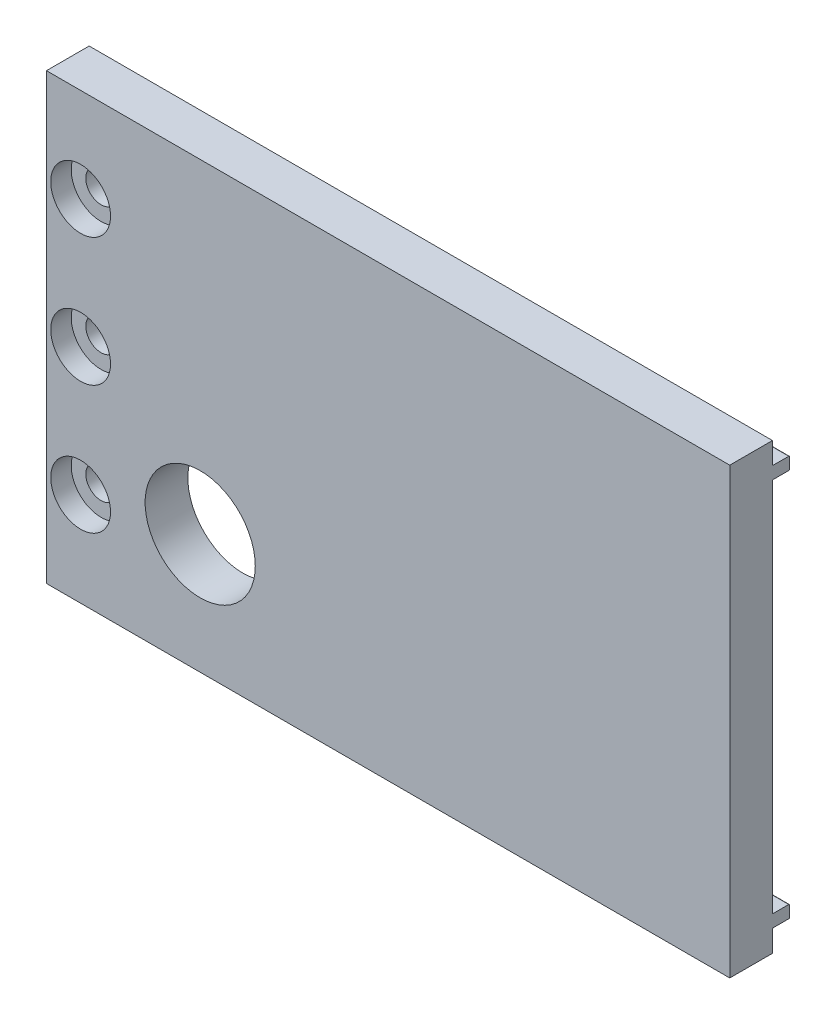
SolidWorks part; units mm, degrees
material "ABS"
ref_plane "Plan de face" through (0, 0, 0) normal (0, 0, 1) x (1, 0, 0)
ref_plane "Plan de dessus" through (0, 0, 0) normal (0, 1, 0) x (1, 0, 0)
ref_plane "Plan de droite" through (0, 0, 0) normal (1, 0, 0) x (0, 0, -1)
sketch "Esquisse1" plane through (0, 0, 16.9801) normal (0, 0, 1) x (1, 0, 0)
  line L1 (-84.4443, 50.0666) -> (-4.4443, 50.0666)
  line L2 (-84.4443, 50.0666) -> (-84.4443, -1.9334)
  line L3 (-84.4443, -1.9334) -> (-4.4443, -1.9334)
  line L4 (-4.4443, 50.0666) -> (-4.4443, -1.9334)
extrude "Boss.-Extru.1" add sketch "Esquisse1" along normal blind 5
sketch "Esquisse2" plane through (0, 0, 21.9801) normal (0, 0, 1) x (1, 0, 0)
  line L0 (-84.4443, 50.0666) -> (-84.4443, -1.9334) construction
  line L1 (-84.4443, -1.9334) -> (-4.4443, -1.9334) construction
  circle A0 centre (-66.4443, 12.0617) radius 6.4479
  dimension "D1" = 12.8957
  dimension "D2" = 18
  dimension "D3" = 13.9952
extrude "Enlèv. mat.-Extru.1" cut sketch "Esquisse2" against normal blind 5
hole_wizard "Chambrage pour vis à tête ronde bombée M34" positions "Esquisse3" profile "Esquisse4" counterbore size "M3" standard "Ansi Metric" end condition up to next
sketch "Esquisse3" plane through (0, 0, 21.9801) normal (0, 0, 1) x (1, 0, 0)
  line L0 (-84.4443, -1.9334) -> (-4.4443, -1.9334) construction
  line L1 (-84.4443, 50.0666) -> (-84.4443, -1.9334) construction
  point P0 (-80.4443, 9.0666)
  point P2 (-80.4443, 24.0666)
  point P4 (-80.4443, 39.0666)
  dimension "D1" = 11
  dimension "D2" = 4
  dimension "D3" = 4
  dimension "D4" = 4
  dimension "D5" = 15
  dimension "D6" = 15
sketch "Esquisse4" plane through (-80.4443, 9.0666, 21.9801) normal (1, 0, 0) x (0, -1, 0)
  line L0 (0, 0) -> (0, 5)
  line L1 (0, 5) -> (1.8, 5)
  line L3 (1.8, 5) -> (1.8, 2.4)
  line L4 (1.8, 2.4) -> (3.5, 2.4)
  line L5 (3.5, 2.4) -> (3.5, 0)
  line L7 (3.5, 0) -> (0, 0)
  line L11 (0, -6.35) -> (0, 107.95) construction
  dimension "Diamètre du perçage jusqu'au prochain" = 3.6
  dimension "Profondeur du perçage jusqu'au prochain" = 5
  dimension "Diamètre du chambrage" = 7
  dimension "Profondeur du chambrage" = 2.4
sketch "Esquisse5" plane through (0, 0, 16.9801) normal (0, 0, -1) x (-1, 0, 0)
  line L0 (4.4443, -1.9334) -> (4.4443, 50.0666) construction
  line L1 (4.4443, 2.0666) -> (76.4443, 2.0666)
  line L2 (4.4443, 2.0666) -> (4.4443, 0.6166)
  line L3 (4.4443, 0.6166) -> (76.4443, 0.6166)
  line L4 (76.4443, 2.0666) -> (76.4443, 0.6166)
  line L5 (84.4443, -1.9334) -> (4.4443, -1.9334) construction
  line L6 (86.3891, 24.0666) -> (2.4995, 24.0666) construction
  line L7 (76.4443, 46.0666) -> (76.4443, 47.5166)
  line L8 (4.4443, 46.0666) -> (4.4443, 47.5166)
  line L9 (4.4443, 47.5166) -> (76.4443, 47.5166)
  line L10 (4.4443, 46.0666) -> (76.4443, 46.0666)
  dimension "D1" = 0
  dimension "D2" = 4
  dimension "D3" = 1.45
  dimension "D4" = 72
extrude "Boss.-Extru.2" add sketch "Esquisse5" along normal blind 2
fillet "Congé1" radius 0.1 8 edges at (-40.4443, 0.6166, 14.9801) (-40.4443, 2.0666, 14.9801) (-40.4443, 47.5166, 14.9801) (-40.4443, 46.0666, 14.9801) (-40.4443, 46.0666, 16.9801) (-40.4443, 47.5166, 16.9801) (-40.4443, 2.0666, 16.9801) (-40.4443, 0.6166, 16.9801)
